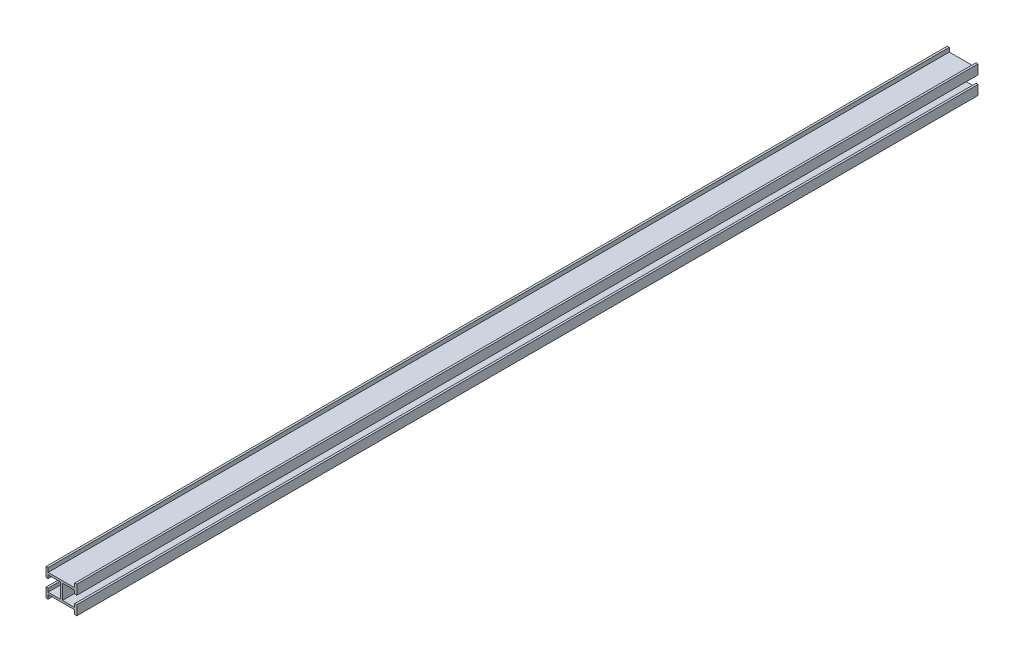
SolidWorks part; units mm, degrees
material "5454-H111"
ref_plane "Front Plane" through (0, 0, 0) normal (0, 0, 1) x (1, 0, 0)
ref_plane "Top Plane" through (0, 0, 0) normal (0, 1, 0) x (1, 0, 0)
ref_plane "Right Plane" through (0, 0, 0) normal (1, 0, 0) x (0, 0, -1)
sketch "Sketch1" plane through (0, 0, 0) normal (0, 0, 1) x (1, 0, 0)
  line L0 (0, 0) -> (0, 119.1208) construction
  line L1 (0, 0) -> (139.1499, 0) construction
  line L2 (-19.5, 14) -> (19.5, 14)
  line L3 (19.5, 14) -> (19.5, 20)
  line L4 (19.5, 20) -> (22.5, 20)
  line L5 (22.5, 20) -> (22.5, 6)
  line L6 (22.5, 6) -> (19.5, 6)
  line L7 (19.5, 6) -> (19.5, 11)
  line L8 (19.5, 11) -> (1.5, 11)
  line L9 (1.5, 11) -> (1.5, -11)
  line L10 (-1.5, 11) -> (-1.5, -11)
  line L11 (-19.5, 11) -> (-1.5, 11)
  line L12 (-19.5, 6) -> (-19.5, 11)
  line L13 (-22.5, 6) -> (-19.5, 6)
  line L14 (-22.5, 20) -> (-22.5, 6)
  line L15 (-19.5, 20) -> (-22.5, 20)
  line L16 (-19.5, 14) -> (-19.5, 20)
  line L17 (-19.5, -14) -> (-19.5, -20)
  line L18 (-19.5, -20) -> (-22.5, -20)
  line L19 (-22.5, -20) -> (-22.5, -6)
  line L20 (-22.5, -6) -> (-19.5, -6)
  line L21 (-19.5, -6) -> (-19.5, -11)
  line L22 (-19.5, -11) -> (-1.5, -11)
  line L23 (19.5, -11) -> (1.5, -11)
  line L24 (19.5, -6) -> (19.5, -11)
  line L25 (22.5, -6) -> (19.5, -6)
  line L26 (22.5, -20) -> (22.5, -6)
  line L27 (19.5, -20) -> (22.5, -20)
  line L28 (19.5, -14) -> (19.5, -20)
  line L29 (-19.5, -14) -> (19.5, -14)
  point P3 (0, -14)
  point P10 (33.0633, 42.7647)
  point P14 (32.3416, 53.1103)
  point P15 (31.8604, 69.2301)
  point P16 (9.0039, 26.4043)
  point P17 (0, 0)
  point P26 (0, 14)
  point P34 (-1.5, 0)
  point P35 (1.5, 0)
  dimension "D1" = 22.5
  dimension "D2" = 20
  dimension "D3" = 1.5
  dimension "D4" = 14
  dimension "D5" = 3
  dimension "D6" = 6
  dimension "D7" = 3
extrude "Boss-Extrude1" add sketch "Sketch1" along normal mid plane 1318 contours L2 L3 L4 L5 L6 L7 L8 L9 L23 L24 L25 L26 L27 L28 L29 L17 L18 L19 L20 L21 L22 L10 L11 L12 L13 L14 L15 L16
